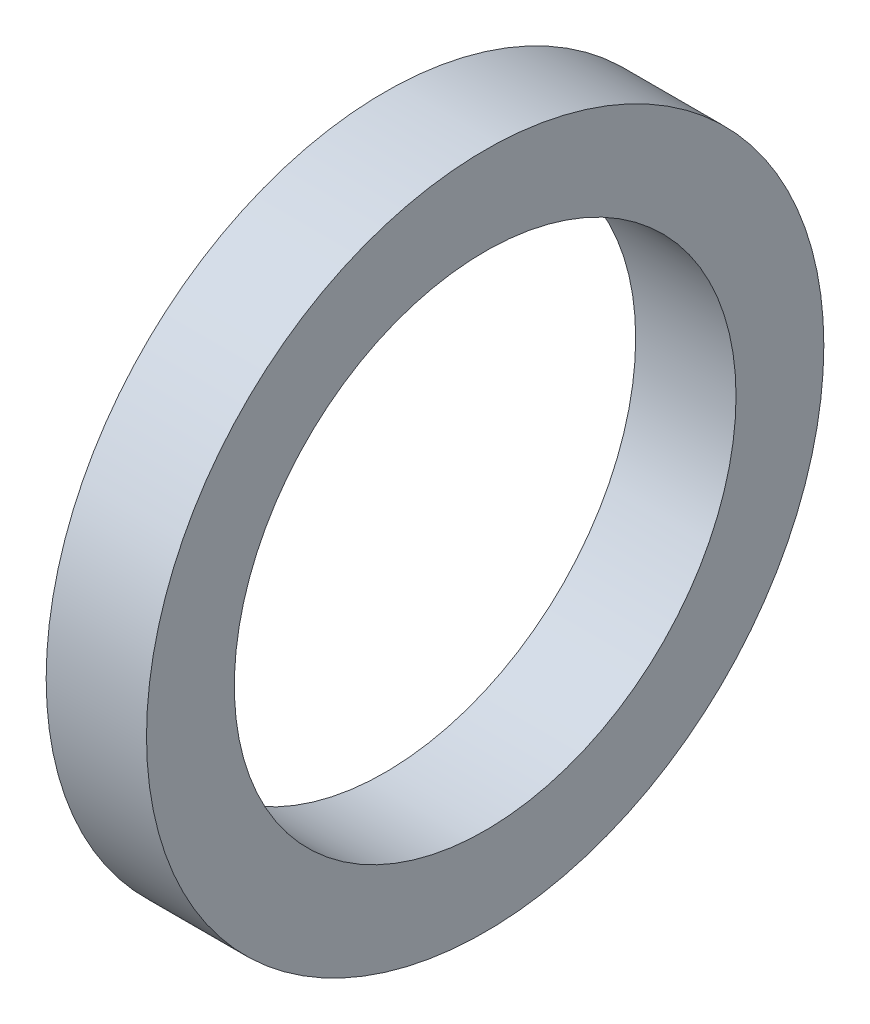
SolidWorks part; units mm, degrees
ref_plane "前视基准面" through (0, 0, 0) normal (0, 0, 1) x (1, 0, 0)
ref_plane "上视基准面" through (0, 0, 0) normal (0, 1, 0) x (1, 0, 0)
ref_plane "右视基准面" through (0, 0, 0) normal (1, 0, 0) x (0, 0, -1)
sketch "草图1" plane through (0, 0, 0) normal (1, 0, 0) x (0, 0, -1)
  circle A0 centre (0, 0) radius 13.5
  circle A1 centre (0, 0) radius 10
  dimension "D1" = 27
  dimension "D2" = 20
extrude "凸台-拉伸1" add sketch "草图1" along normal mid plane 4
